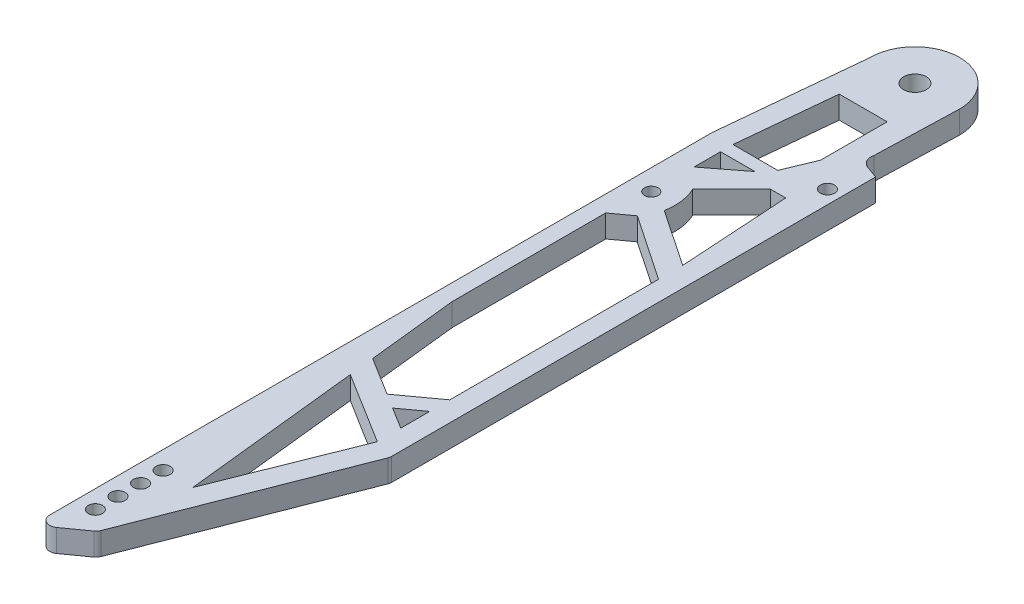
SolidWorks part; units mm, degrees
material "6061-T6 (SS)"
ref_plane "X-Y Datum" through (0, 0, 0) normal (0, 0, 1) x (1, 0, 0)
ref_plane "X-Z Datum" through (0, 0, 0) normal (0, 1, 0) x (1, 0, 0)
ref_plane "Y-Z Datum" through (0, 0, 0) normal (1, 0, 0) x (0, 0, -1)
other "Graphic1" [suppressed]
other "Graphic (Closed) -1" [suppressed]
sketch "Sketch2" plane through (0, 0, 0) normal (0, 1, 0) x (1, 0, 0)
  line L5 (-12.5603, 0) -> (-12.5603, -63.5) construction
  line L8 (0, 0) -> (0, -24.13) construction
  line L11 (0, -24.13) -> (18.0975, -24.13) construction
  line L14 (13.8466, -27.1172) -> (17.2959, -28.3595)
  line L15 (-16.51, -231.775) -> (-16.51, -118.11)
  line L18 (-16.51, -118.11) -> (-16.51, -40.5272)
  line L19 (-16.51, -40.5272) -> (-12.5603, 0)
  line L20 (11.8343, -23.3926) -> (12.5603, 0)
  line L21 (-16.51, -231.775) -> (-5.7887, -224.1061)
  line L22 (-5.7887, -224.1061) -> (17.2959, -164.9508)
  line L23 (17.2959, -164.9508) -> (17.2959, -28.3595)
  line L31 (-3.0884, -200.025) -> (-8.4371, -150.3674)
  line L32 (-8.4371, -150.3674) -> (11.7079, -162.9144)
  line L33 (11.7079, -162.9144) -> (-3.0884, -200.025)
  line L34 (5.6698, -152.5704) -> (11.7079, -156.3311)
  line L35 (11.7079, -156.3311) -> (11.7079, -148.1732)
  line L36 (11.7079, -148.1732) -> (5.6698, -152.5704)
  line L37 (-9.1972, -143.3108) -> (1.4836, -149.9631)
  line L38 (1.4836, -149.9631) -> (11.7079, -142.5174)
  line L39 (11.7079, -142.5174) -> (11.7079, -83.8261)
  line L40 (11.7079, -83.8261) -> (-6.7526, -71.3454)
  line L41 (-6.7526, -71.3454) -> (-11.8945, -75.0899)
  line L42 (-11.8945, -75.0899) -> (-11.8945, -118.2685)
  line L43 (-11.8945, -118.2685) -> (-9.1972, -143.3108)
  line L44 (-5.4504, -57.0473) -> (5.4772, -46.1198)
  line L45 (5.4772, -46.1198) -> (9.7706, -46.1198)
  line L46 (9.7706, -46.1198) -> (11.7079, -77.0374)
  line L47 (11.7079, -77.0374) -> (-4.2406, -66.255)
  line L49 (-10.6553, -40.5272) -> (-8.0015, -13.2972)
  line L50 (-8.0015, -13.2972) -> (5.4772, -13.2972)
  line L51 (5.4772, -13.2972) -> (5.4772, -31.9741)
  line L52 (5.4772, -31.9741) -> (1.9411, -40.5272)
  line L53 (1.9411, -40.5272) -> (-10.6553, -40.5272)
  line L54 (-10.6553, -44.0228) -> (-10.6553, -51.4721)
  line L55 (-10.6553, -51.4721) -> (-0.9913, -44.0228)
  line L56 (-0.9913, -44.0228) -> (-10.6553, -44.0228)
  circle A0 centre (0, 0) radius 3.175
  circle A2 centre (-11.43, -219.075) radius 2
  circle A3 centre (-11.43, -212.725) radius 2
  circle A4 centre (-11.43, -206.375) radius 2
  circle A5 centre (-11.43, -200.025) radius 2
  circle A7 centre (0, 0) radius 12.5603 construction
  circle A8 centre (-10.6553, -63.5) radius 1.905
  circle A9 centre (14.9225, -24.13) radius 3.175 construction
  arc A11 (13.8466, -27.1172) -> (11.8343, -23.3926) centre (14.9225, -24.13) cw
  circle A12 centre (13.4859, -38.1) radius 2
  arc A13 (-12.5603, 0) -> (12.5603, 0) centre (0, 0) cw
  arc A14 (-4.2406, -66.255) -> (-5.4504, -57.0473) centre (-18.9173, -63.5) ccw
  circle A15 centre (13.7795, -24.8261) radius 3.175 construction
  point P32 (18.0975, -24.13)
  dimension "D1" = 6.35
  dimension "D6" = 4
  dimension "D12" = 24.13
  dimension "D5" = 25.1206
  dimension "D14" = 3.81
  dimension "D19" = 4
  dimension "D20" = 6.35
  dimension "D24" = 6.148
  dimension "D50" = 14.933
  dimension "D51" = 8.262
  dimension "D42" = 6.35
  dimension "D3" = 40.7192
  dimension "D7" = 6.35
  dimension "D8" = 6.35
  dimension "D9" = 6.35
  dimension "D10" = 5.08
  dimension "D11" = 12.7
  dimension "D13" = 18.0975
  dimension "D15" = 77.5828
  dimension "D16" = 63.5
  dimension "D17" = 23.4039
  dimension "D18" = 63.5
  dimension "D21" = 136.5913
  dimension "D22" = 38.1
  dimension "D23" = 13.1818
  dimension "D25" = 8.0729
  dimension "D26" = 3.81
  dimension "D27" = 3.6662
  dimension "D28" = 40.5272
  dimension "D29" = 5.588
  dimension "D30" = 39.9516
  dimension "D31" = 5.1419
  dimension "D32" = 43.1786
  dimension "D33" = 185.566
  dimension "D34" = 54.424
  dimension "D35" = 5.624
  dimension "D36" = 5.588
  dimension "D37" = 247.98
  dimension "D38" = 12.6481
  dimension "D39" = 22.2836
  dimension "D40" = 51.936
  dimension "D41" = 4.572
  dimension "D43" = 200.025
  dimension "D44" = 1.143
  dimension "D45" = 4.6155
  dimension "D46" = 52.353
  dimension "D47" = 4.2935
  dimension "D48" = 135
  dimension "D49" = 15.4539
  dimension "D52" = 27.359
  dimension "D53" = 5.8271
  dimension "D54" = 18.6769
  dimension "D55" = 157.539
  dimension "D56" = 3.4956
  dimension "D57" = 52.374
  dimension "D58" = 12.0279
  dimension "D59" = 0.6961
extrude "Boss-Extrude1" add sketch "Sketch2" along normal blind 6.35
fillet "Fillet3" radius 2.54 1 edges at (-5.7887, 3.175, 224.1061)
fillet "Fillet4" radius 2.54 1 edges at (-16.51, 3.175, 231.775)
fillet "Fillet5" radius 2.54 1 edges at (17.2959, 3.175, 164.9508)
